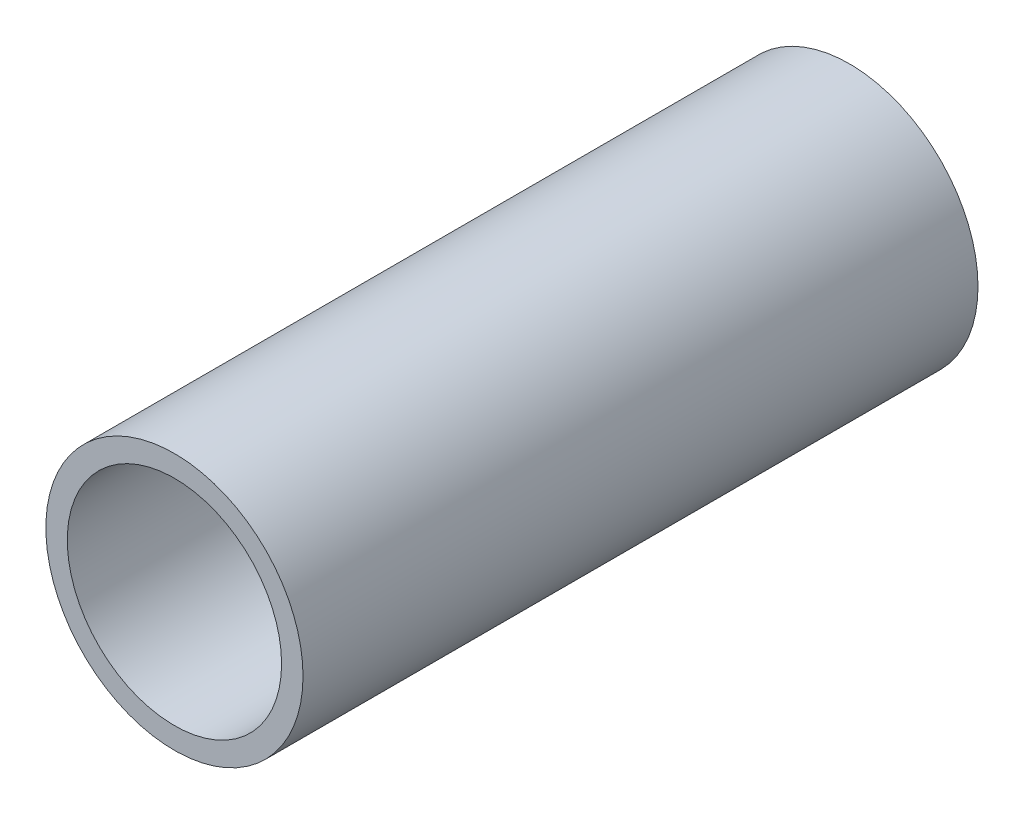
SolidWorks part; units mm, degrees
material "Acrylic (Medium-high impact)"
ref_plane "Front Plane" through (0, 0, 0) normal (0, 0, 1) x (1, 0, 0)
ref_plane "Top Plane" through (0, 0, 0) normal (0, 1, 0) x (1, 0, 0)
ref_plane "Right Plane" through (0, 0, 0) normal (1, 0, 0) x (0, 0, -1)
sketch "Sketch1" plane through (0, 0, 0) normal (0, 0, 1) x (1, 0, 0)
  circle A0 centre (0, 0) radius 19.05
  dimension "D1" = 38.1
extrude "Extrude-Thin1" add sketch "Sketch1" against normal blind 100 thin thin type one direction reverse wall 3.175
